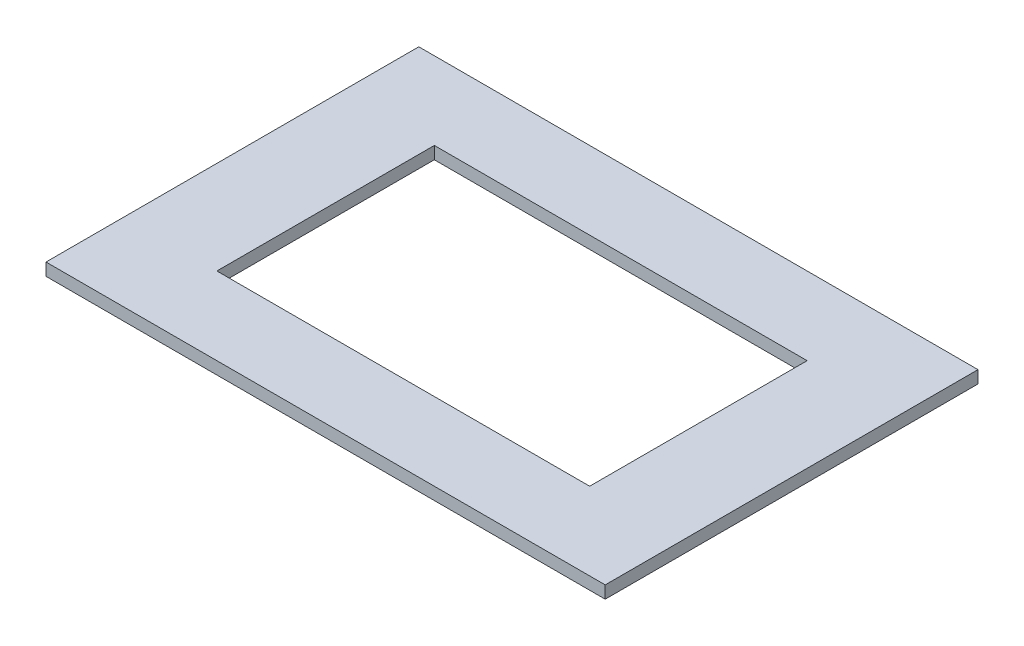
SolidWorks part; units mm, degrees
ref_plane "Plano frontal" through (0, 0, 0) normal (0, 0, 1) x (1, 0, 0)
ref_plane "Plano superior" through (0, 0, 0) normal (0, 1, 0) x (1, 0, 0)
ref_plane "Plano direito" through (0, 0, 0) normal (1, 0, 0) x (0, 0, -1)
sketch "Esboço1" plane through (0, 0, 0) normal (0, 1, 0) x (1, 0, 0)
  line L0 (0, 0) -> (0, 180)
  line L1 (0, 180) -> (270, 180)
  line L2 (270, 180) -> (270, 0)
  line L3 (270, 0) -> (0, 0)
  line L4 (45, 142.5) -> (45, 37.5)
  line L5 (45, 37.5) -> (225, 37.5)
  line L6 (225, 37.5) -> (225, 142.5)
  line L7 (225, 142.5) -> (45, 142.5)
  dimension "D1" = 270
  dimension "D2" = 180
  dimension "D3" = 180
  dimension "D4" = 45
  dimension "D5" = 45
  dimension "D6" = 105
  dimension "D7" = 37.5
  dimension "D8" = 37.5
extrude "Ressalto-extrusão1" add sketch "Esboço1" along normal blind 6
